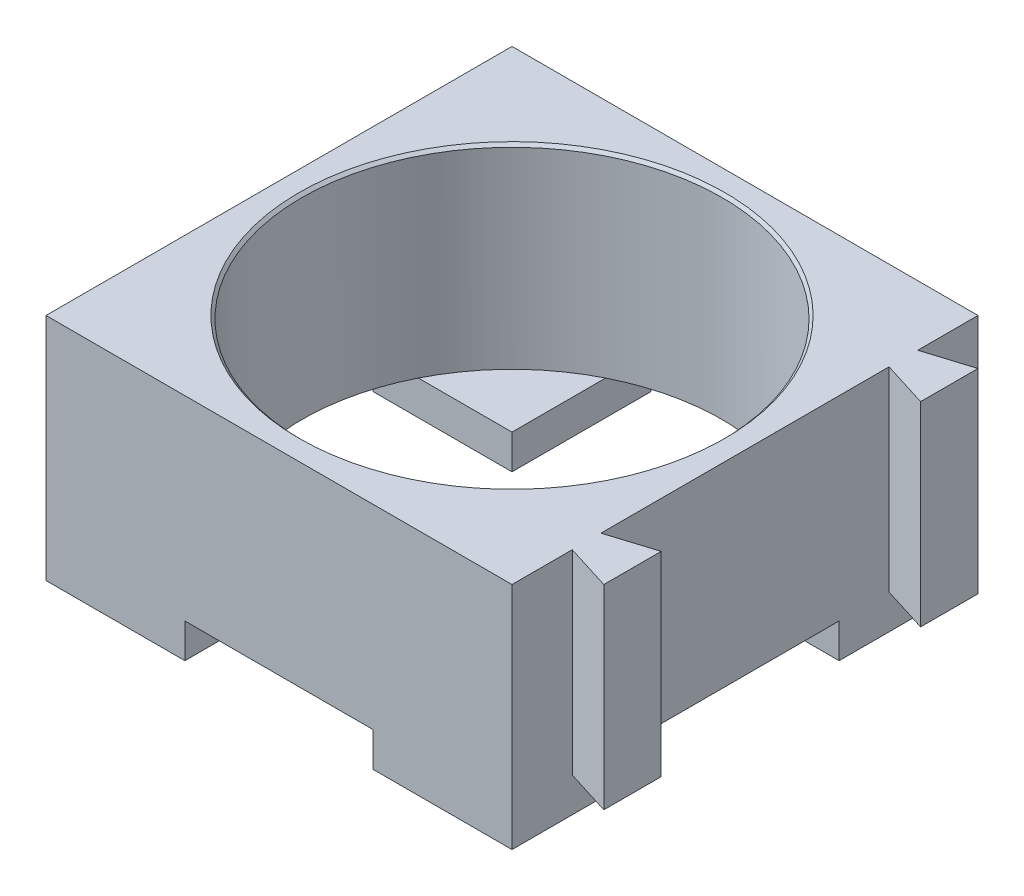
SolidWorks part; units mm, degrees
ref_plane "Front Plane" through (0, 0, 0) normal (0, 0, 1) x (1, 0, 0)
ref_plane "Top Plane" through (0, 0, 0) normal (0, 1, 0) x (1, 0, 0)
ref_plane "Right Plane" through (0, 0, 0) normal (1, 0, 0) x (0, 0, -1)
sketch "Sketch1" plane through (0, 0, 0) normal (0, 1, 0) x (1, 0, 0)
  line L0 (12.15, 8.15) -> (12.15, 5.65)
  line L1 (-10.15, 10.15) -> (10.15, 10.15)
  line L2 (-10.15, 10.15) -> (-10.15, -10.15)
  line L3 (-10.15, -10.15) -> (10.15, -10.15)
  line L4 (10.15, 10.15) -> (10.15, 7.525)
  line L5 (-10.15, 10.15) -> (10.15, -10.15) construction
  line L6 (-10.15, -10.15) -> (10.15, 10.15) construction
  line L7 (12.15, 5.65) -> (10.15, 6.275)
  line L8 (12.15, 8.15) -> (10.15, 7.525)
  line L9 (12.15, -5.65) -> (10.15, -6.275)
  line L10 (12.15, -5.65) -> (12.15, -8.15)
  line L11 (12.15, -8.15) -> (10.15, -7.525)
  line L12 (10.15, 6.275) -> (10.15, -6.275)
  line L13 (10.15, -7.525) -> (10.15, -10.15)
  circle A0 centre (0, 0) radius 9.15
  point P12 (12.15, 6.9)
  dimension "D1" = 18.3
  dimension "D2" = 20.3
  dimension "D3" = 20.3
  dimension "D4" = 2.5
  dimension "D5" = 1.25
  dimension "D6" = 0.625
  dimension "D7" = 2
  dimension "D8" = 2
  dimension "D10" = 2
  dimension "D9" = 2
extrude "Cell Holder " add sketch "Sketch1" along normal blind 8.5
sketch "Sketch2" plane through (0, 0, 0) normal (0, -1, 0) x (1, 0, 0)
  line L1 (-10.15, 10.15) -> (-4.1, 10.15)
  line L2 (-10.15, 10.15) -> (-10.15, 4.1)
  line L3 (-10.15, 4.1) -> (-4.1, 4.1)
  line L4 (-4.1, 10.15) -> (-4.1, 4.1)
  line L5 (-10.15, -10.15) -> (-4.1, -10.15)
  line L6 (-10.15, -10.15) -> (-10.15, -4.1)
  line L7 (-10.15, -4.1) -> (-4.1, -4.1)
  line L8 (-4.1, -10.15) -> (-4.1, -4.1)
  line L9 (10.15, 10.15) -> (4.1, 10.15)
  line L10 (10.15, 10.15) -> (10.15, 4.1)
  line L11 (10.15, 4.1) -> (4.1, 4.1)
  line L12 (4.1, 10.15) -> (4.1, 4.1)
  line L13 (10.15, -10.15) -> (4.1, -10.15)
  line L14 (10.15, -10.15) -> (10.15, -4.1)
  line L15 (10.15, -4.1) -> (4.1, -4.1)
  line L16 (4.1, -10.15) -> (4.1, -4.1)
  circle A0 centre (0, 0) radius 9.15 construction
  dimension "D1" = 8.2
  dimension "D2" = 4.1
  dimension "D3" = 8.2
  dimension "D4" = 4.1
extrude "Bottom Base Boss" add sketch "Sketch2" along normal blind 1.5
chamfer "Chamfer1" distance 0.125 angle 45 1 edges at (0, 8.5, 9.15)
